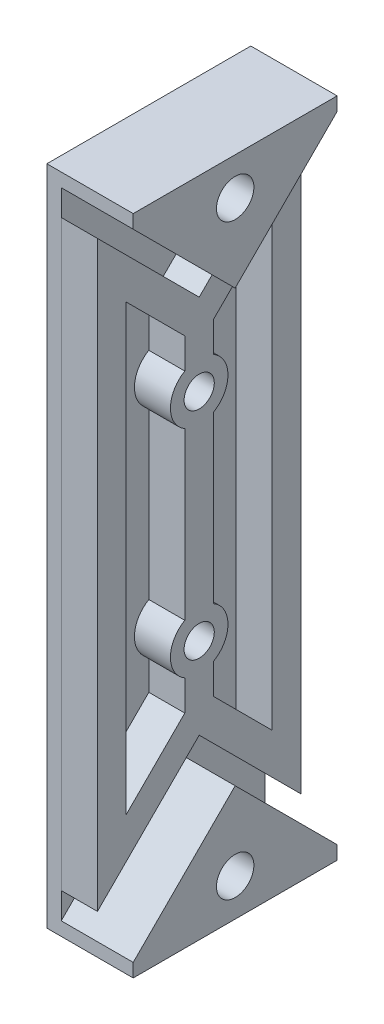
SolidWorks part; units mm, degrees
ref_plane "Front Plane" through (0, 0, 0) normal (0, 0, 1) x (1, 0, 0)
ref_plane "Top Plane" through (0, 0, 0) normal (0, 1, 0) x (1, 0, 0)
ref_plane "Right Plane" through (0, 0, 0) normal (1, 0, 0) x (0, 0, -1)
sketch "Sketch1" plane through (0, 0, 0) normal (1, 0, 0) x (0, 0, -1)
  line L0 (14.1421, 0) -> (14.1421, -81) construction
  line L1 (0, 0) -> (28.2843, 0)
  line L2 (0, 0) -> (0, -81)
  line L3 (0, -81) -> (28.2843, -81)
  line L4 (28.2843, 0) -> (28.2843, -81)
  line L5 (0, 0) -> (14.1421, -14.1421)
  line L6 (14.1421, -14.1421) -> (28.2843, 0)
  line L7 (0, -40.5) -> (28.2843, -40.5) construction
  line L8 (14.1421, -66.8579) -> (28.2843, -81)
  line L9 (0, -81) -> (14.1421, -66.8579)
  dimension "D1" = 45
  dimension "D2" = 20
  dimension "D3" = 81
extrude "Boss-Extrude1" add sketch "Sketch1" along normal blind 5 contours L2 L9 L8 L4 L6 L5
sketch "Sketch2" plane through (5, 0, 0) normal (1, 0, 0) x (0, 0, -1)
  line L6 (14.1421, -14.1421) -> (14.1421, -66.8579) construction
  line L8 (12.1421, -65.5) -> (16.1421, -65.5)
  line L9 (12.1421, -65.5) -> (12.1421, -15.5)
  line L10 (12.1421, -15.5) -> (16.1421, -15.5)
  line L11 (16.1421, -65.5) -> (16.1421, -15.5)
  line L12 (4, -9.6569) -> (4, -71.3431)
  line L13 (4, -71.3431) -> (14.1421, -61.201)
  line L14 (14.1421, -61.201) -> (24.2843, -71.3431)
  line L15 (24.2843, -71.3431) -> (24.2843, -9.6569)
  line L16 (24.2843, -9.6569) -> (14.1421, -19.799)
  line L17 (14.1421, -19.799) -> (4, -9.6569)
  line L18 (4, -9.6569) -> (4, -71.3431)
  line L19 (4, -71.3431) -> (14.1421, -61.201)
  line L20 (14.1421, -61.201) -> (24.2843, -71.3431)
  line L21 (24.2843, -71.3431) -> (24.2843, -9.6569)
  line L22 (24.2843, -9.6569) -> (14.1421, -19.799)
  line L23 (14.1421, -19.799) -> (4, -9.6569)
  line L24 (12.1421, -65.5) -> (16.1421, -15.5) construction
  line L25 (12.1421, -15.5) -> (16.1421, -65.5) construction
  point P3 (14.1421, -40.5)
  dimension "D2" = 50
  dimension "D3" = 4
  dimension "D1" = 4
extrude "Cut-Extrude1" cut sketch "Sketch2" against normal through all contours L9 L23 L18 L19 | L21 L22 L11 L20
sketch "Sketch3" plane through (5, 0, 0) normal (1, 0, 0) x (0, 0, -1)
  line L0 (0, 0) -> (1.7961, 1.7961)
  line L1 (1.7961, 1.7961) -> (14.1421, -10.55)
  line L2 (14.1421, -10.55) -> (26.4882, 1.7961)
  line L3 (0, 0) -> (14.1421, -14.1421) construction
  line L4 (14.1421, -14.1421) -> (28.2843, 0) construction
  line L5 (26.4882, 1.7961) -> (28.2843, 0)
  line L6 (0, -40.5) -> (28.2843, -40.5) construction
  line L7 (0, 0) -> (0, -81) construction
  line L8 (28.2843, 0) -> (28.2843, -81) construction
  line L9 (0, 0) -> (14.1421, -14.1421)
  line L10 (-0.0279, -86.5) -> (28.3121, -86.5)
  line L11 (-0.0279, -86.5) -> (-0.0279, 5.5)
  line L12 (-0.0279, 5.5) -> (28.3121, 5.5)
  line L13 (28.3121, -86.5) -> (28.3121, 5.5)
  line L14 (-0.0279, -86.5) -> (28.3121, 5.5) construction
  line L15 (-0.0279, 5.5) -> (28.3121, -86.5) construction
  line L16 (14.1421, -14.1421) -> (28.2843, 0)
  line L17 (28.2843, 0) -> (28.3511, -0.0096)
  line L18 (0, -81) -> (14.1421, -66.8579)
  line L19 (0, -81) -> (1.7961, -82.7961)
  line L20 (1.7961, -82.7961) -> (14.1421, -70.45)
  line L21 (14.1421, -70.45) -> (26.4882, -82.7961)
  line L22 (26.4882, -82.7961) -> (28.2843, -81)
  line L23 (14.1421, -66.8579) -> (28.2843, -81)
  line L24 (28.2843, -81) -> (28.3511, -80.9904)
  line L25 (0, 0) -> (0, -81)
  line L26 (28.2843, -81) -> (28.3511, -0.0096)
  line L27 (1.7961, 1.7961) -> (-0.0279, 3.62)
  line L28 (26.4882, 1.7961) -> (28.3121, 3.62)
  line L29 (1.7961, -82.7961) -> (-0.0279, -84.62)
  line L30 (26.4882, -82.7961) -> (28.3121, -84.62)
  point P17 (14.1421, -40.5)
  dimension "D1" = 2.54
  dimension "D2" = 2.54
  dimension "D3" = 90
  dimension "D4" = 90
  dimension "D5" = 28.34
  dimension "D6" = 92
  dimension "D7" = 180
extrude "Boss-Extrude6" add sketch "Sketch3" against normal blind 5 separate body contours L2 L28 L13 L12 L11 L27 L1 | L30 L21 L20 L29 L11 L10 L13
sketch "Sketch4" plane through (0, 0, 0) normal (-1, 0, 0) x (0, 0, 1)
  line L1 (-28.3121, 5.5) -> (0.0279, 5.5)
  line L2 (-28.3121, 5.5) -> (-28.3121, -86.5)
  line L3 (-28.3121, -86.5) -> (0.0279, -86.5)
  line L4 (0.0279, 5.5) -> (0.0279, -86.5)
extrude "Boss-Extrude7" add sketch "Sketch4" along normal blind 2
sketch "Sketch5" plane through (5, 0, 0) normal (1, 0, 0) x (0, 0, -1)
  line L0 (14.1421, 5.5) -> (14.1421, -86.5) construction
  line L1 (-0.0279, 5.5) -> (28.3121, 5.5) construction
  line L2 (-0.0279, -86.5) -> (28.3121, -86.5) construction
  line L3 (0, -40.5) -> (28.2843, -40.5) construction
  line L4 (0, 0) -> (0, -81) construction
  line L5 (28.2843, 0) -> (28.2843, -81) construction
  circle A0 centre (14.1421, 0.3) radius 2.6
  circle A1 centre (14.1421, -81.3) radius 2.6
  dimension "D1" = 5.2
  dimension "D2" = 5.2
extrude "Cut-Extrude2" cut sketch "Sketch5" against normal through all
sketch "Sketch6" plane through (5, 0, 0) normal (1, 0, 0) x (0, 0, -1)
  line L0 (28.2843, -40.5) -> (0, -40.5) construction
  line L1 (28.2843, 0) -> (28.2843, -81) construction
  line L2 (0, 0) -> (0, -81) construction
  line L3 (14.1421, -14.1421) -> (14.1421, -66.8579) construction
  circle A0 centre (14.1421, -55.5) radius 4
  circle A1 centre (14.1421, -25.5) radius 4
  dimension "D1" = 30
  dimension "D2" = 15
  dimension "D3" = 8
  dimension "D4" = 8
extrude "Boss-Extrude8" add sketch "Sketch6" against normal through all
sketch "Sketch7" plane through (5, 0, 0) normal (1, 0, 0) x (0, 0, -1)
  circle A0 centre (14.1421, -25.5) radius 2.1
  circle A1 centre (14.1421, -55.5) radius 2.1
  dimension "D1" = 4.2
  dimension "D2" = 4.2
extrude "Cut-Extrude4" cut sketch "Sketch7" against normal through all
sketch "Sketch8" plane through (5, 0, 0) normal (1, 0, 0) x (0, 0, -1)
  line L0 (28.3121, 5.5) -> (28.3121, 3.62)
  line L1 (28.3121, 3.62) -> (14.1421, -10.55)
  line L2 (14.1421, -10.55) -> (-0.0279, 3.62)
  line L3 (-0.0279, 3.62) -> (-0.0279, 5.5)
  line L4 (-0.0279, 5.5) -> (28.3121, 5.5)
  line L5 (28.2843, -40.5) -> (0, -40.5) construction
  line L6 (28.2843, 0) -> (28.2843, -81) construction
  line L7 (0, 0) -> (0, -81) construction
  line L8 (28.3121, -86.5) -> (28.3121, -84.62)
  line L9 (-0.0279, -86.5) -> (28.3121, -86.5)
  line L10 (-0.0279, -84.62) -> (-0.0279, -86.5)
  line L11 (14.1421, -70.45) -> (-0.0279, -84.62)
  line L12 (28.3121, -84.62) -> (14.1421, -70.45)
  circle A0 centre (14.1421, 0.3) radius 2.6
  circle A1 centre (14.1421, -81.3) radius 2.6
extrude "Boss-Extrude9" add sketch "Sketch8" along normal blind 5
